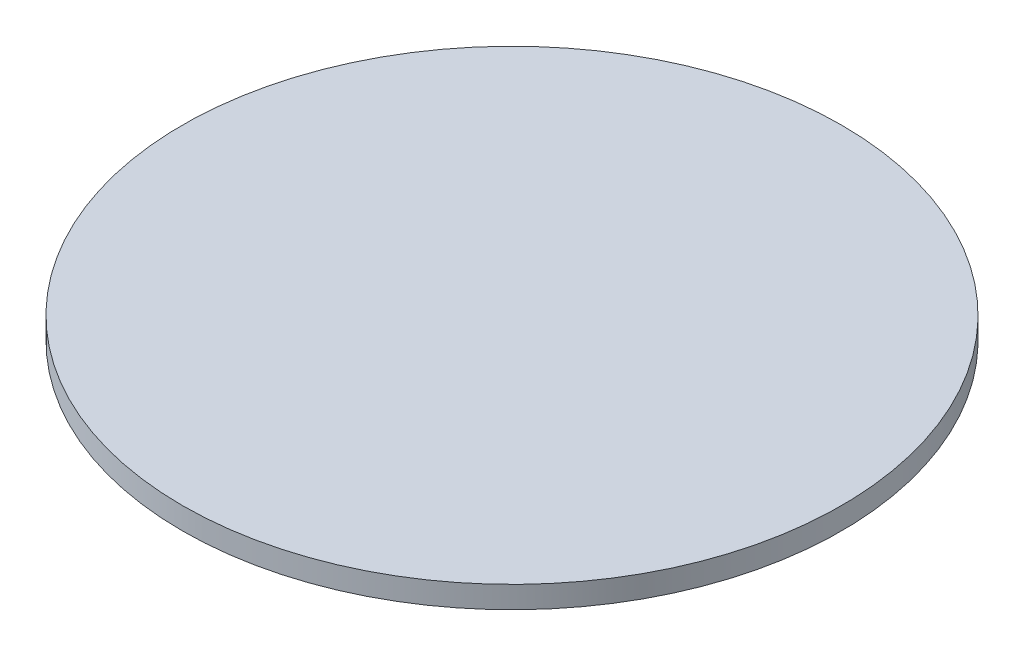
SolidWorks part; units mm, degrees
ref_plane "正面" through (0, 0, 0) normal (0, 0, 1) x (1, 0, 0)
ref_plane "平面" through (0, 0, 0) normal (0, 1, 0) x (1, 0, 0)
ref_plane "右側面" through (0, 0, 0) normal (1, 0, 0) x (0, 0, -1)
sketch "ｽｹｯﾁ3" plane through (0, 0, 0) normal (0, 1, 0) x (1, 0, 0)
  circle A0 centre (0, 0) radius 150
  dimension "D1" = 300
extrude "ﾎﾞｽ - 押し出し2" add sketch "ｽｹｯﾁ3" along normal blind 10
